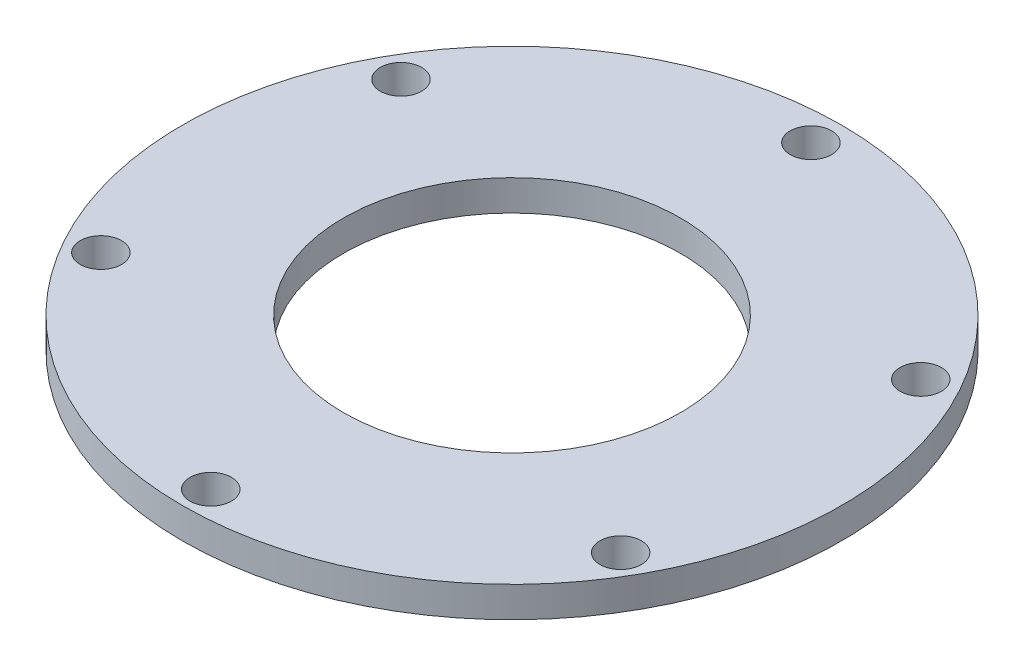
SolidWorks part; units mm, degrees
ref_plane "Alzado" through (0, 0, 0) normal (0, 0, 1) x (1, 0, 0)
ref_plane "Planta" through (0, 0, 0) normal (0, 1, 0) x (1, 0, 0)
ref_plane "Vista lateral" through (0, 0, 0) normal (1, 0, 0) x (0, 0, -1)
sketch "Croquis1" plane through (0, 0, 0) normal (0, 1, 0) x (1, 0, 0)
  circle A0 centre (0, 0) radius 107.5
  dimension "D1" = 215
extrude "Saliente-Extruir1" add sketch "Croquis1" along normal blind 10
sketch "Croquis2" plane through (0, 10, 0) normal (0, 1, 0) x (1, 0, 0)
  circle A0 centre (0, 0) radius 97.5
  dimension "D1" = 195
sketch "Croquis4" plane through (0, 10, 0) normal (0, 1, 0) x (1, 0, 0)
  circle A0 centre (0, 0) radius 55
  dimension "D1" = 110
sketch "Croquis5" plane through (0, 10, 0) normal (0, 1, 0) x (1, 0, 0)
  line L0 (0, 0) -> (0, 129.5423)
hole_wizard "Taladro de margen para M121" positions "Croquis3D1" profile "Croquis6" hole size "M12" standard "Ansi Metric"
sketch3d "Croquis3D1"
  line L0 (0, 10, 0) -> (0, 10, -129.5423) construction
  circle A0 centre (0, 10, 0) radius 97.5 construction
  point P0 (0, 10, -97.5)
  point P4 (0, 107.5, 0)
sketch "Croquis6" plane through (0, 10, -97.5) normal (1, 0, 0) x (0, 0, 1)
  line L0 (0, 0) -> (0, 47.5558)
  line L1 (0, 47.5558) -> (6.75, 43.5)
  line L2 (6.75, 43.5) -> (6.75, 0)
  line L5 (6.75, 0) -> (0, 0)
  line L10 (0, 47.5558) -> (-6.75, 43.5) construction
  line L11 (0, -6.35) -> (0, 107.95) construction
  dimension "Diámetro de taladro" = 13.5
  dimension "Profundidad de taladro" = 43.5
  dimension "Ángulo de perforador" = 118
pattern_circular "MatrizC1" count 6 over 360 about axis through (0, 0, 0.3859) along (0, 1, 0) of "Taladro de margen para M121"
extrude "Cortar-Extruir1" cut sketch "Croquis4" against normal blind 10 contours A0
